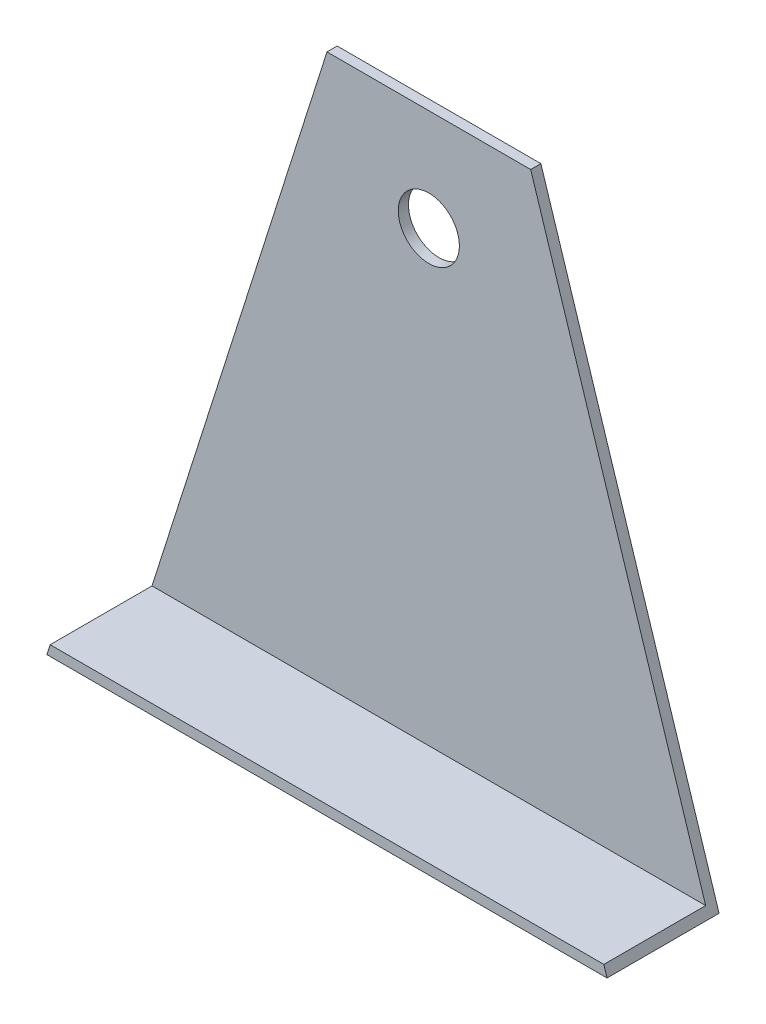
SolidWorks part; units mm, degrees
ref_plane "Front Plane" through (0, 0, 0) normal (0, 0, 1) x (1, 0, 0)
ref_plane "Top Plane" through (0, 0, 0) normal (0, 1, 0) x (1, 0, 0)
ref_plane "Right Plane" through (0, 0, 0) normal (1, 0, 0) x (0, 0, -1)
sketch "Sketch1" plane through (0, 0, 0) normal (0, 0, 1) x (1, 0, 0)
  line L0 (-55, 0) -> (55, 0)
  line L1 (55, 0) -> (20, 110)
  line L2 (20, 110) -> (-20, 110)
  line L3 (-20, 110) -> (-55, 0)
  line L4 (0, 0) -> (0, 136.8511) construction
  dimension "D1" = 55
  dimension "D2" = 55
  dimension "D3" = 110
  dimension "D4" = 40
  dimension "D5" = 20
extrude "Boss-Extrude1" add sketch "Sketch1" along normal blind 2
sketch "Sketch2" plane through (0, 0, 2) normal (0, 0, 1) x (1, 0, 0)
  line L0 (-55, 0) -> (55, 0) construction
  circle A0 centre (0, 90) radius 6
  dimension "D1" = 12
  dimension "D2" = 90
extrude "Cut-Extrude1" cut sketch "Sketch2" against normal through all
sketch "Sketch4" plane through (0, 0, 2) normal (0, 0, 1) x (1, 0, 0)
  line L0 (-55, 0) -> (-54.3636, 2)
  line L1 (-20, 110) -> (-55, 0) construction
  line L2 (-54.3636, 2) -> (54.3636, 2)
  line L3 (55, 0) -> (20, 110) construction
  line L4 (54.3636, 2) -> (55, 0)
  line L5 (55, 0) -> (-55, 0)
  dimension "D1" = 2
extrude "Boss-Extrude2" add sketch "Sketch4" along normal blind 20
sketch "Sketch5" plane through (0, 2, 0) normal (0, 1, 0) x (1, 0, 0)
  line L0 (0, 0) -> (0, -22) construction
  line L1 (54.3636, -22) -> (-54.3636, -22) construction
sketch "Sketch6" plane through (0, 0, 0) normal (0, 0, -1) x (-1, 0, 0)
  line L0 (0, 110) -> (0, 0) construction
  line L1 (-20, 110) -> (20, 110) construction
